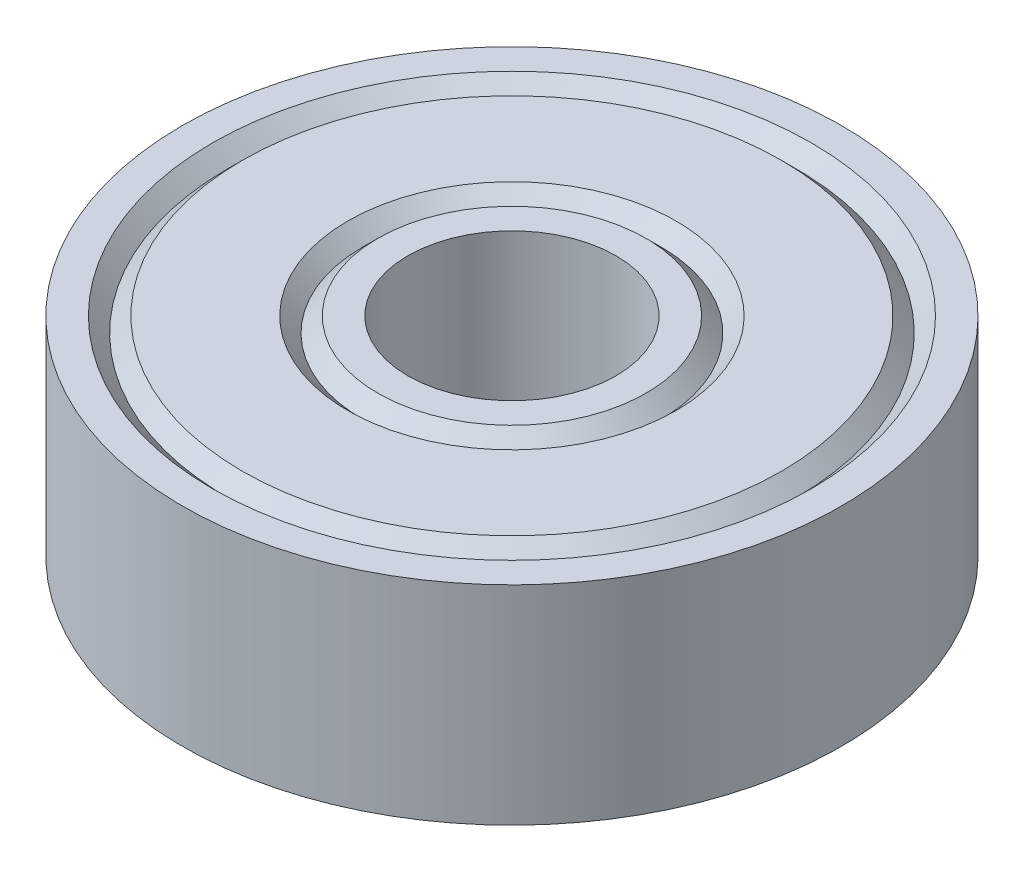
SolidWorks part; units mm, degrees
ref_plane "Front Plane" through (0, 0, 0) normal (0, 0, 1) x (1, 0, 0)
ref_plane "Top Plane" through (0, 0, 0) normal (0, 1, 0) x (1, 0, 0)
ref_plane "Right Plane" through (0, 0, 0) normal (1, 0, 0) x (0, 0, -1)
sketch "Sketch1" plane through (0, 0, 0) normal (0, 0, 1) x (1, 0, 0)
  line L0 (0, 3) -> (0, -3) construction
  line L1 (-3, 3) -> (-3.8667, 3)
  line L2 (-3, 3) -> (-3, -3)
  line L3 (-3, -3) -> (-3.8667, -3)
  line L4 (-9.5, 3) -> (-9.5, -3)
  line L5 (-8.6333, 3) -> (-8.2, 2.5667)
  line L6 (-8.2, 2.5667) -> (-7.7667, 3)
  line L7 (-4.7333, 3) -> (-4.3, 2.5667)
  line L8 (-4.3, 2.5667) -> (-3.8667, 3)
  line L9 (-8.6333, -3) -> (-8.2, -2.5667)
  line L10 (-8.2, -2.5667) -> (-7.7667, -3)
  line L11 (-4.7333, -3) -> (-4.3, -2.5667)
  line L12 (-4.3, -2.5667) -> (-3.8667, -3)
  line L13 (-4.7333, -3) -> (-7.7667, -3)
  line L14 (-8.6333, -3) -> (-9.5, -3)
  line L15 (-8.6333, 3) -> (-9.5, 3)
  line L16 (-4.7333, 3) -> (-7.7667, 3)
  line L17 (-8.2, 2.5667) -> (-4.3, 2.5667) construction
  line L18 (-8.2, 2.5667) -> (-8.2, -2.5667) construction
  line L19 (-4.3, -2.5667) -> (-8.2, -2.5667) construction
  line L20 (-4.3, 2.5667) -> (-4.3, -2.5667) construction
  line L21 (-8.2, 0) -> (-6.9, 0) construction
  line L22 (-3.8667, 3) -> (-4.7333, 3) construction
  line L23 (-6.9, 0) -> (-5.6, 0) construction
  line L24 (-8.2, 0) -> (-9.5, 0) construction
  line L25 (-5.6, 0) -> (-4.3, 0) construction
  line L26 (-4.3, 0) -> (-3, 0) construction
  dimension "D1" = 6
  dimension "D2" = 6
  dimension "D3" = 19
revolve "Revolve1" add sketch "Sketch1" angle 360 about L0
